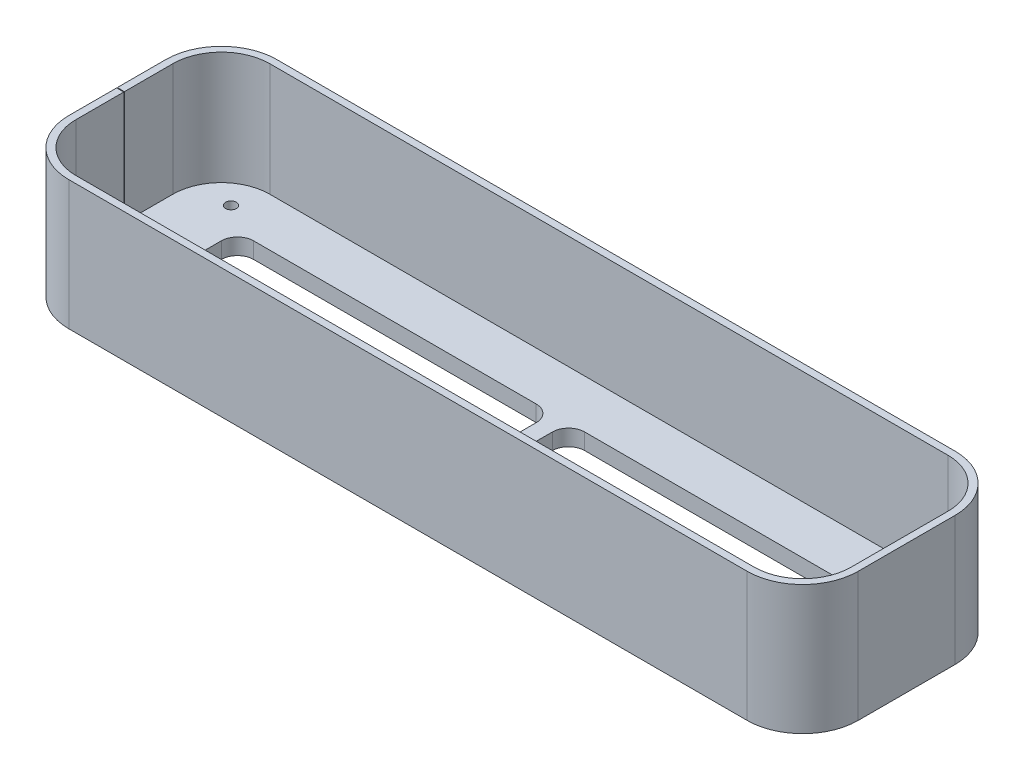
SolidWorks part; units mm, degrees
material "Acrylic (Medium-high impact)"
ref_plane "Front" through (0, 0, 0) normal (0, 0, 1) x (1, 0, 0)
ref_plane "Top" through (0, 0, 0) normal (0, 1, 0) x (1, 0, 0)
ref_plane "Right" through (0, 0, 0) normal (1, 0, 0) x (0, 0, -1)
sketch "Sketch6" [suppressed] plane through (0, 0, 0) normal (0, 0, 1) x (1, 0, 0)
  line L1 (0, 0) -> (736.6, 0)
  line L2 (0, 0) -> (0, -50.8)
  line L3 (0, -50.8) -> (736.6, -50.8)
  line L4 (736.6, 0) -> (736.6, -50.8)
  dimension "D1" = 50.8
  dimension "D2" = 736.6
extrude "Boss-Extrude4" [suppressed] add sketch "Sketch6" along normal blind 2.794
sketch "Sketch1" plane through (0, 0, 0) normal (0, 1, 0) x (1, 0, 0)
  line L1 (-152.4, 38.1) -> (152.4, 38.1)
  line L2 (-152.4, 38.1) -> (-152.4, -38.1)
  line L3 (-152.4, -38.1) -> (152.4, -38.1)
  line L4 (152.4, 38.1) -> (152.4, -38.1)
  line L5 (-152.4, 38.1) -> (152.4, -38.1) construction
  line L6 (-152.4, -38.1) -> (152.4, 38.1) construction
  point P0 (0, 0)
  dimension "D1" = 304.8
  dimension "D2" = 76.2
extrude "Boss-Extrude1" add sketch "Sketch1" along normal blind 6.35
sketch "Sketch2" plane through (0, 6.35, 0) normal (0, 1, 0) x (1, 0, 0)
  line L0 (152.4, -38.1) -> (152.4, 38.1) construction
  line L1 (-127, 19.05) -> (127, 19.05)
  line L2 (-127, 19.05) -> (-127, -19.05)
  line L3 (-127, -19.05) -> (127, -19.05)
  line L4 (127, 19.05) -> (127, -19.05)
  line L5 (-127, 19.05) -> (127, -19.05) construction
  line L6 (-127, -19.05) -> (127, 19.05) construction
  point P0 (0, 0)
  point P6 (127, 0)
  dimension "D1" = 38.1
  dimension "D2" = 25.4
extrude "Cut-Extrude1" cut sketch "Sketch2" against normal through all
sketch "Sketch3" plane through (0, 6.35, 0) normal (0, 1, 0) x (1, 0, 0)
  line L0 (-127, -19.05) -> (127, -19.05) construction
  line L1 (-3.175, 19.05) -> (3.175, 19.05)
  line L2 (-3.175, 19.05) -> (-3.175, -19.05)
  line L3 (-3.175, -19.05) -> (3.175, -19.05)
  line L4 (3.175, 19.05) -> (3.175, -19.05)
  line L5 (-3.175, 19.05) -> (3.175, -19.05) construction
  line L6 (-3.175, -19.05) -> (3.175, 19.05) construction
  point P0 (0, 0)
  dimension "D1" = 6.35
extrude "Boss-Extrude2" add sketch "Sketch3" against normal up to surface (6.35 mm away) up to face at (0, 0, 0)
fillet "Fillet1" radius 19.05 4 edges at (152.4, 3.175, -38.1) (152.4, 3.175, 38.1) (-152.4, 3.175, 38.1) (-152.4, 3.175, -38.1)
fillet "Fillet2" radius 6.35 8 edges at (3.175, 3.175, 19.05) (3.175, 3.175, -19.05) (127, 3.175, -19.05) (127, 3.175, 19.05) (-3.175, 3.175, 19.05) (-3.175, 3.175, -19.05) (-127, 3.175, -19.05) (-127, 3.175, 19.05)
sketch "Sketch4" plane through (0, 6.35, 0) normal (0, 1, 0) x (1, 0, 0)
  line L0 (133.35, 38.1) -> (-133.35, 38.1) construction
  line L1 (-137.16, 26.67) -> (137.16, 26.67) construction
  line L2 (-137.16, 26.67) -> (-137.16, -26.67) construction
  line L3 (-137.16, -26.67) -> (137.16, -26.67) construction
  line L4 (137.16, 26.67) -> (137.16, -26.67) construction
  line L5 (-137.16, 26.67) -> (137.16, -26.67) construction
  line L6 (-137.16, -26.67) -> (137.16, 26.67) construction
  line L7 (152.4, -19.05) -> (152.4, 19.05) construction
  circle A0 centre (137.16, 26.67) radius 2.14
  circle A1 centre (137.16, -26.67) radius 2.14
  circle A2 centre (-137.16, -26.67) radius 2.14
  circle A3 centre (-137.16, 26.67) radius 2.14
  point P0 (0, 0)
  dimension "D3" = 4.2799
  dimension "D1" = 11.43
  dimension "D2" = 15.24
extrude "Cut-Extrude2" cut sketch "Sketch4" against normal through all
sketch "Sketch5" plane through (0, 0, 0) normal (0, 1, 0) x (1, 0, 0)
  line L0 (-155.194, 19.05) -> (-155.194, 0)
  line L1 (-133.35, -40.894) -> (133.35, -40.894)
  line L2 (155.194, -19.05) -> (155.194, 19.05)
  line L3 (133.35, 40.894) -> (-133.35, 40.894)
  line L4 (152.4, -19.05) -> (152.4, 19.05)
  line L5 (133.35, 38.1) -> (-133.35, 38.1)
  line L6 (-152.4, 19.05) -> (-152.4, -19.05)
  line L7 (-133.35, -38.1) -> (133.35, -38.1)
  line L8 (152.4, -19.05) -> (152.4, 19.05)
  line L9 (133.35, 38.1) -> (-133.35, 38.1)
  line L10 (-152.4, 19.05) -> (-152.4, 0)
  line L11 (-133.35, -38.1) -> (133.35, -38.1)
  line L12 (-152.4, 0) -> (-155.194, 0)
  line L13 (-152.4, -0.254) -> (-155.194, -0.254)
  line L14 (-155.194, -0.254) -> (-155.194, -19.05)
  line L15 (-155.194, 19.05) -> (-155.194, -19.05) construction
  line L16 (-152.4, -0.254) -> (-152.4, -19.05)
  line L17 (-152.4, 19.05) -> (-152.4, -19.05) construction
  arc A0 (-133.35, 40.894) -> (-155.194, 19.05) centre (-133.35, 19.05) ccw
  arc A1 (-155.194, -19.05) -> (-133.35, -40.894) centre (-133.35, -19.05) ccw
  arc A2 (133.35, -40.894) -> (155.194, -19.05) centre (133.35, -19.05) ccw
  arc A3 (155.194, 19.05) -> (133.35, 40.894) centre (133.35, 19.05) ccw
  arc A4 (152.4, 19.05) -> (133.35, 38.1) centre (133.35, 19.05) ccw
  arc A5 (-133.35, 38.1) -> (-152.4, 19.05) centre (-133.35, 19.05) ccw
  arc A6 (-152.4, -19.05) -> (-133.35, -38.1) centre (-133.35, -19.05) ccw
  arc A7 (133.35, -38.1) -> (152.4, -19.05) centre (133.35, -19.05) ccw
  arc A8 (152.4, 19.05) -> (133.35, 38.1) centre (133.35, 19.05) ccw
  arc A9 (-133.35, 38.1) -> (-152.4, 19.05) centre (-133.35, 19.05) ccw
  arc A10 (-152.4, -19.05) -> (-133.35, -38.1) centre (-133.35, -19.05) ccw
  arc A11 (133.35, -38.1) -> (152.4, -19.05) centre (133.35, -19.05) ccw
  dimension "D3" = 0.254
  dimension "D4" = 38.1
  dimension "D1" = 0
  dimension "D2" = 2.794
extrude "Boss-Extrude3" add sketch "Sketch5" along normal blind 50.8 separate body
